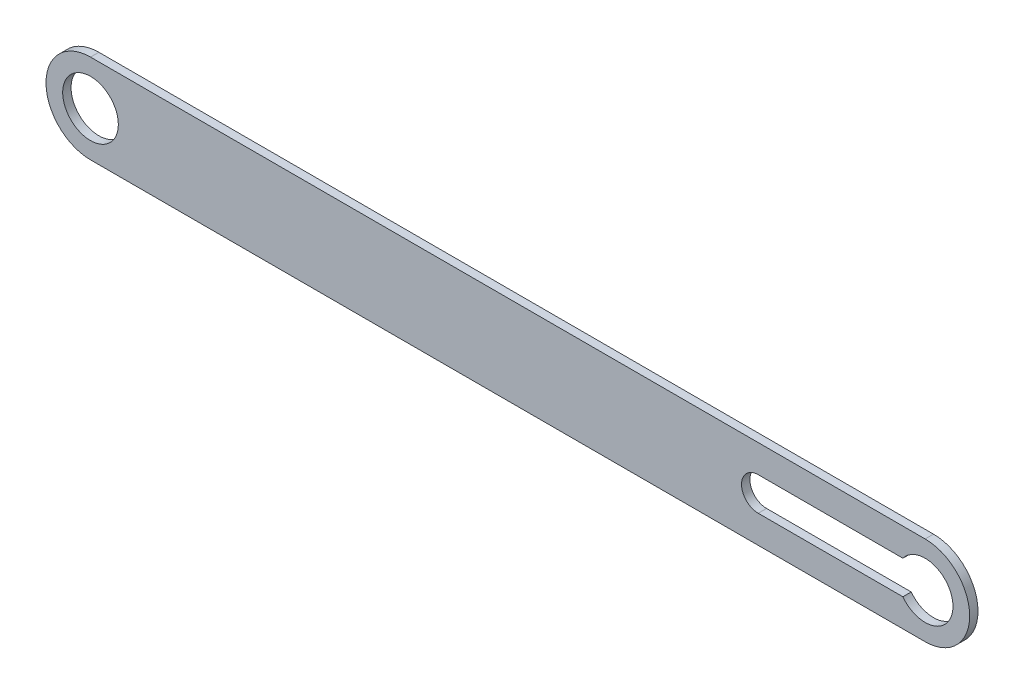
SolidWorks part; units mm, degrees
ref_plane "Front Plane" through (0, 0, 0) normal (0, 0, 1) x (1, 0, 0)
ref_plane "Top Plane" through (0, 0, 0) normal (0, 1, 0) x (1, 0, 0)
ref_plane "Right Plane" through (0, 0, 0) normal (1, 0, 0) x (0, 0, -1)
sketch "Sketch1" plane through (0, 0, 0) normal (0, 0, 1) x (1, 0, 0)
  line L0 (-75, 0) -> (70, 0) construction
  line L1 (-75, 8) -> (75, 8)
  line L2 (-75, -8) -> (75, -8)
  line L3 (70, 0) -> (45, 0) construction
  line L4 (71, -3) -> (45, -3)
  line L5 (71, 3) -> (45, 3)
  arc A0 (-75, 8) -> (-75, -8) centre (-75, 0) ccw
  arc A1 (75, -8) -> (75, 8) centre (75, 0) ccw
  arc A2 (71, -3) -> (71, 3) centre (75, 0) ccw
  circle A3 centre (-75, 0) radius 5
  arc A5 (45, 3) -> (45, -3) centre (45, 0) ccw
  point P2 (0, 0)
  point P12 (60, 0)
  dimension "D2" = 16
  dimension "D3" = 10
  dimension "D4" = 10
  dimension "D1" = 150
  dimension "D5" = 30
  dimension "D6" = 6
extrude "Boss-Extrude1" add sketch "Sketch1" along normal blind 1.5
